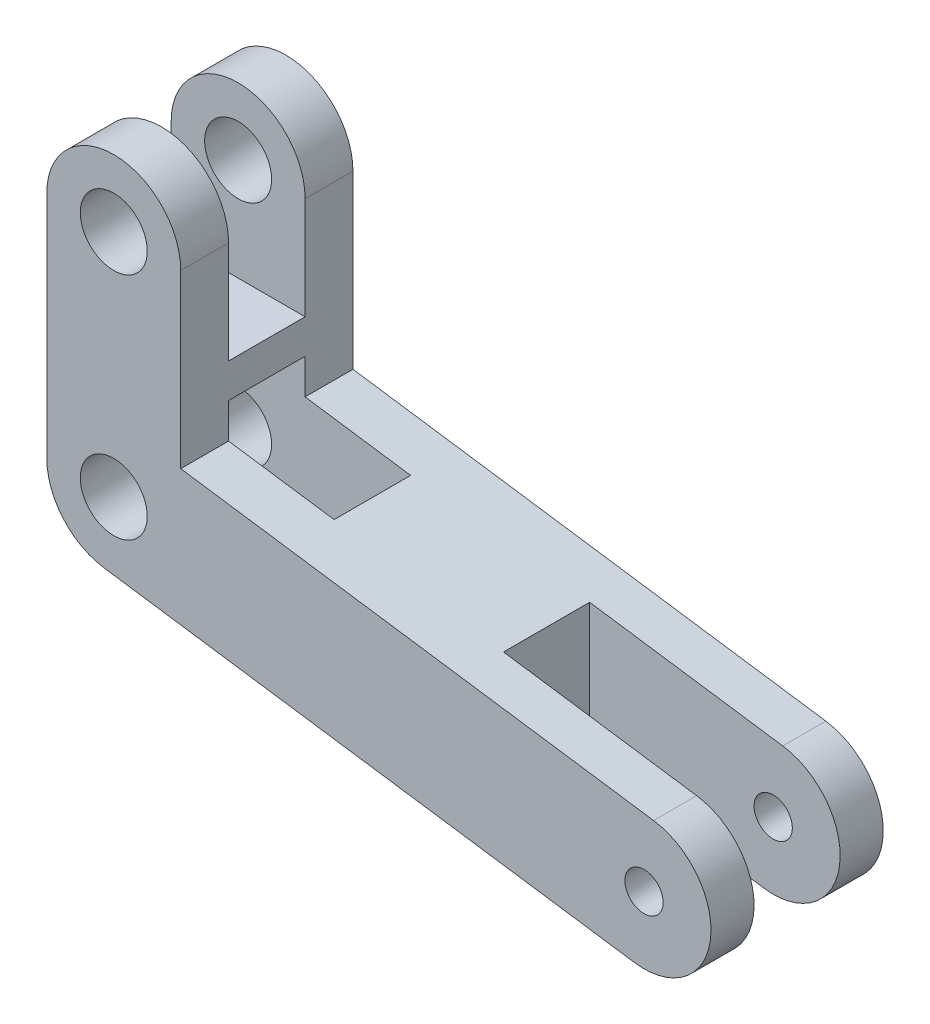
SolidWorks part; units mm, degrees
ref_plane "前视基准面" through (0, 0, 0) normal (0, 0, 1) x (1, 0, 0)
ref_plane "上视基准面" through (0, 0, 0) normal (0, 1, 0) x (1, 0, 0)
ref_plane "右视基准面" through (0, 0, 0) normal (1, 0, 0) x (0, 0, -1)
other "Configuration Table"
sketch "草图1" plane through (0, 0, 0) normal (0, 0, 1) x (1, 0, 0)
  line L0 (0, 12) -> (0, 1.75) construction
  line L1 (27.2128, -7.4641) -> (-0.5, -3.4641)
  line L2 (-3.5, 12) -> (-3.5, 0)
  line L3 (3.5, 12) -> (3.5, 3.0311)
  line L8 (28.2128, -0.5359) -> (3.5, 3.0311)
  line L9 (27.7128, -3) -> (27.7128, -4) construction
  circle A0 centre (0, 0) radius 1.75
  arc A1 (-3.5, 0) -> (-0.5, -3.4641) centre (0, 0) ccw
  arc A2 (3.5, 12) -> (-3.5, 12) centre (0, 12) ccw
  circle A4 centre (0, 12) radius 1.75
  arc A5 (27.2128, -7.4641) -> (28.2128, -0.5359) centre (27.7128, -4) ccw
  circle A6 centre (27.7128, -4) radius 1
  dimension "D1" = 12
  dimension "D2" = 3.5
  dimension "D3" = 7
  dimension "D8" = 2
  dimension "D4" = 28
  dimension "D5" = 4
extrude "凸台-拉伸1" add sketch "草图1" along normal mid plane 9
sketch "草图5" plane through (0, 0, 0) normal (0, 0, 1) x (1, 0, 0)
  line L1 (-5.6997, 16.4699) -> (3.5, 16.4699)
  line L2 (-5.6997, 16.4699) -> (-5.6997, 6.6567)
  line L3 (-5.6997, 6.6567) -> (3.5, 6.6567)
  line L4 (3.5, 16.4699) -> (3.5, 6.6567)
  line L5 (-5.6455, -5.6561) -> (9.0148, -5.6561)
  line L6 (-5.6455, -5.6561) -> (-5.6455, 4.8693)
  line L7 (-5.6455, 4.8693) -> (9.0148, 4.8693)
  line L8 (9.0148, -5.6561) -> (9.0148, 4.8693)
extrude "切除-拉伸3" cut sketch "草图5" against normal mid plane 4
sketch "草图6" plane through (0, 0, 0) normal (0, 0, 1) x (1, 0, 0)
  line L1 (37.3062, -10) -> (18.1194, -10)
  line L2 (37.3062, -10) -> (37.3062, 2)
  line L3 (37.3062, 2) -> (18.1194, 2)
  line L4 (18.1194, -10) -> (18.1194, 2)
  line L5 (37.3062, -10) -> (18.1194, 2) construction
  line L6 (37.3062, 2) -> (18.1194, -10) construction
  point P0 (27.7128, -4)
  dimension "D1" = 6
extrude "切除-拉伸4" cut sketch "草图6" against normal mid plane 4.5
